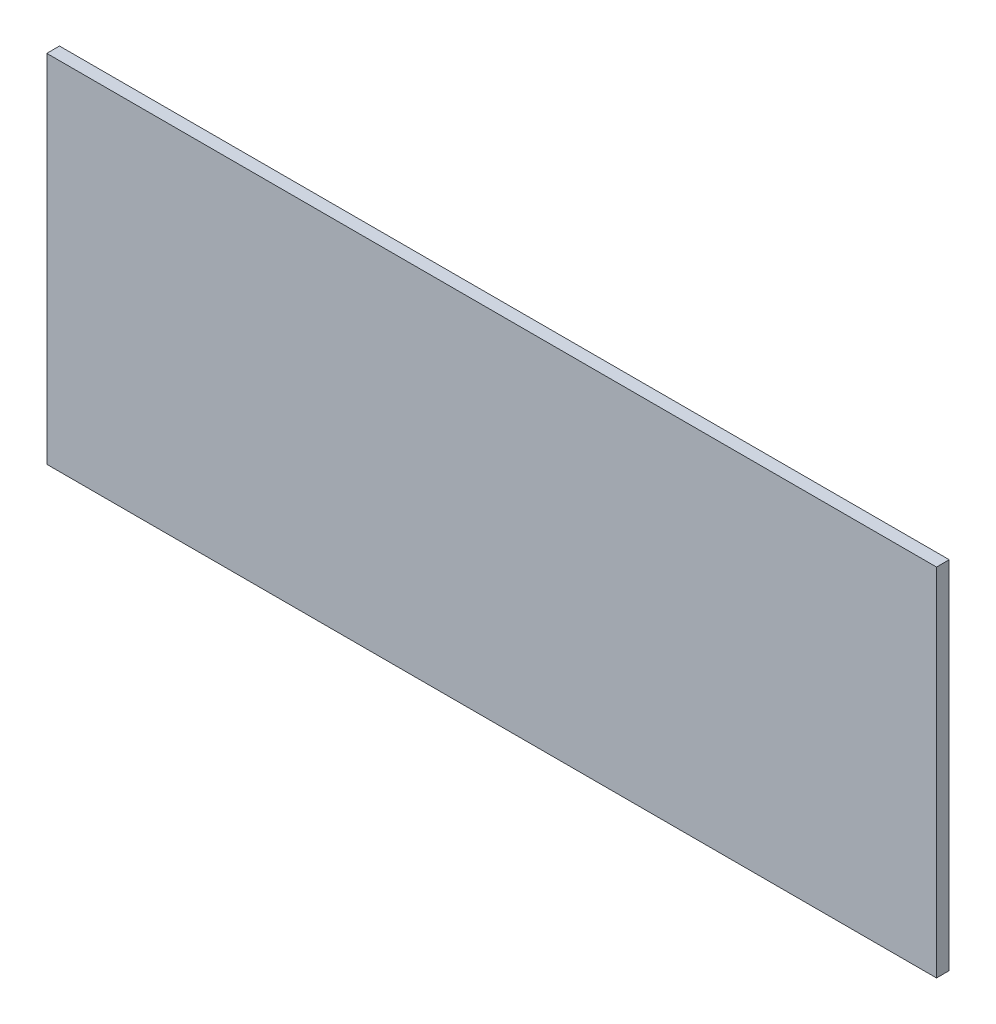
SolidWorks part; units mm, degrees
ref_plane "Alzado" through (0, 0, 0) normal (0, 0, 1) x (1, 0, 0)
ref_plane "Planta" through (0, 0, 0) normal (0, 1, 0) x (1, 0, 0)
ref_plane "Vista lateral" through (0, 0, 0) normal (1, 0, 0) x (0, 0, -1)
sketch "Croquis3" plane through (0, 0, 0) normal (0, 0, 1) x (1, 0, 0)
  line L2 (-90.5016, 84) -> (119.4984, 84)
  line L3 (-90.5016, 84) -> (-90.5016, 0)
  line L4 (-90.5016, 0) -> (119.4984, 0)
  line L5 (119.4984, 84) -> (119.4984, 0)
  dimension "D1" = 84
  dimension "D2" = 210
extrude "Saliente-Extruir2" add sketch "Croquis3" against normal blind 3
